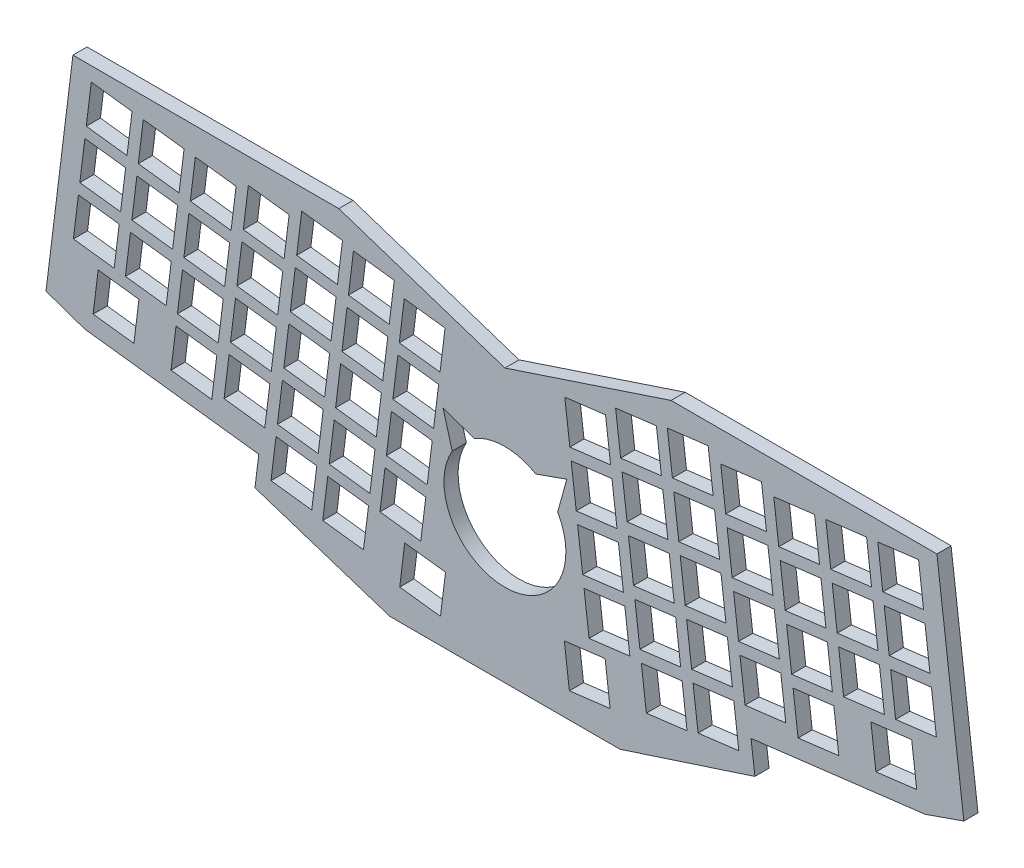
SolidWorks part; units mm, degrees
ref_plane "Спереди" through (0, 0, 0) normal (0, 0, 1) x (1, 0, 0)
ref_plane "Сверху" through (0, 0, 0) normal (0, 1, 0) x (1, 0, 0)
ref_plane "Справа" through (0, 0, 0) normal (1, 0, 0) x (0, 0, -1)
sketch "Контур" plane through (0, 0, 0) normal (0, 0, 1) x (1, 0, 0)
  line L0 (148.3547, -23.6716) -> (86.886, -31.2162)
  line L1 (162, -18.92) -> (148.3547, -23.6716)
  line L2 (-152.5, 58) -> (-58.64, 58)
  line L3 (86.886, -31.2162) -> (88.2371, -42.1562)
  line L4 (-10.9082, 11.6263) -> (-21.8482, 15.5133)
  line L5 (152.5, 58) -> (162, -18.92)
  line L6 (-88.2371, -42.1562) -> (-40.5971, -57.6623)
  line L7 (-58.64, 58) -> (0, 38.59)
  line L8 (-152.5, 58) -> (-162, -18.92)
  line L9 (58.64, 58) -> (0, 38.59)
  line L10 (-86.886, -31.2162) -> (-88.2371, -42.1562)
  line L11 (-40.5971, -57.6623) -> (40.5971, -57.6623)
  line L12 (-162, -18.92) -> (-148.3547, -23.6716)
  line L13 (0, 0) -> (0, -106.1018) construction
  line L14 (-148.3547, -23.6716) -> (-86.886, -31.2162)
  line L15 (88.2371, -42.1562) -> (40.5971, -57.6623)
  line L16 (152.5, 58) -> (58.64, 58)
  line L17 (-21.8482, 15.5133) -> (-18.6176, 3.8733)
  line L18 (21.8482, 15.5133) -> (18.6176, 3.8733)
  line L19 (10.9082, 11.6263) -> (21.8482, 15.5133)
  arc A0 (-18.6176, 3.8733) -> (18.6176, 3.8733) centre (0, -6.93) ccw
  arc A2 (10.9082, 11.6263) -> (-10.9082, 11.6263) centre (0, -6.93) ccw
  point P0 (0, 0)
  point P19 (0, -57.6623)
  dimension "D1" = 43.05
  dimension "D2" = 10.94
  dimension "D3" = 61.4687
  dimension "D6" = 47.64
  dimension "D7" = 50.1
  dimension "D8" = 11.64
  dimension "D9" = 12.08
  dimension "D10" = 11.61
  dimension "D11" = 45.52
sketch "Эскиз4" plane through (0, 0, 0) normal (0, 0, 1) x (1, 0, 0)
  line L0 (21.8482, 15.5133) -> (18.6176, 3.8733) construction
  line L1 (10.9082, 11.6263) -> (21.8482, 15.5133) construction
  line L2 (-10.9082, 11.6263) -> (-21.8482, 15.5133) construction
  line L3 (-21.8482, 15.5133) -> (-18.6176, 3.8733) construction
  line L4 (21.8482, 15.5133) -> (18.6176, 3.8733)
  line L5 (10.9082, 11.6263) -> (21.8482, 15.5133)
  line L6 (-10.9082, 11.6263) -> (-21.8482, 15.5133)
  line L7 (-21.8482, 15.5133) -> (-18.6176, 3.8733)
  line L12 (-21.8482, 15.5133) -> (-18.6176, 3.8733)
  line L13 (-21.8482, 15.5133) -> (-18.6176, 3.8733)
  line L14 (-10.9082, 11.6263) -> (-21.8482, 15.5133)
  line L15 (152.5, 58) -> (58.64, 58)
  line L16 (58.64, 58) -> (0, 38.59)
  line L17 (0, 38.59) -> (-58.64, 58)
  line L18 (-58.64, 58) -> (-152.5, 58)
  line L19 (-152.5, 58) -> (-162, -18.92)
  line L20 (-162, -18.92) -> (-148.3547, -23.6716)
  line L21 (-148.3547, -23.6716) -> (-86.886, -31.2162)
  line L22 (-86.886, -31.2162) -> (-88.2371, -42.1562)
  line L23 (-88.2371, -42.1562) -> (-40.5971, -57.6623)
  line L24 (-40.5971, -57.6623) -> (40.5971, -57.6623)
  line L25 (40.5971, -57.6623) -> (88.2371, -42.1562)
  line L26 (88.2371, -42.1562) -> (86.886, -31.2162)
  line L27 (86.886, -31.2162) -> (148.3547, -23.6716)
  line L28 (148.3547, -23.6716) -> (162, -18.92)
  line L29 (162, -18.92) -> (152.5, 58)
  line L30 (152.5, 58) -> (58.64, 58)
  line L31 (58.64, 58) -> (0, 38.59)
  line L32 (0, 38.59) -> (-58.64, 58)
  line L33 (-58.64, 58) -> (-152.5, 58)
  line L34 (-152.5, 58) -> (-162, -18.92)
  line L35 (-162, -18.92) -> (-148.3547, -23.6716)
  line L36 (-148.3547, -23.6716) -> (-86.886, -31.2162)
  line L37 (-86.886, -31.2162) -> (-88.2371, -42.1562)
  line L38 (-88.2371, -42.1562) -> (-40.5971, -57.6623)
  line L39 (-40.5971, -57.6623) -> (40.5971, -57.6623)
  line L40 (40.5971, -57.6623) -> (88.2371, -42.1562)
  line L41 (88.2371, -42.1562) -> (86.886, -31.2162)
  line L42 (86.886, -31.2162) -> (148.3547, -23.6716)
  line L43 (148.3547, -23.6716) -> (162, -18.92)
  line L44 (162, -18.92) -> (152.5, 58)
  line L45 (-10.9082, 11.6263) -> (-21.8482, 15.5133)
  line L46 (21.8482, 15.5133) -> (10.9082, 11.6263)
  line L47 (21.8482, 15.5133) -> (10.9082, 11.6263)
  line L48 (18.6176, 3.8733) -> (21.8482, 15.5133)
  line L49 (18.6176, 3.8733) -> (21.8482, 15.5133)
  arc A1 (-18.6176, 3.8733) -> (18.6176, 3.8733) centre (0, -6.93) ccw
  arc A2 (-18.6176, 3.8733) -> (18.6176, 3.8733) centre (0, -6.93) ccw
  arc A3 (10.9082, 11.6263) -> (-10.9082, 11.6263) centre (0, -6.93) ccw
  arc A6 (10.9082, 11.6263) -> (-10.9082, 11.6263) centre (0, -6.93) ccw
  arc A7 (10.9082, 11.6263) -> (-10.9082, 11.6263) centre (0, -6.93) ccw
  dimension "D1" = 0
  dimension "D2" = 0
extrude "Бобышка-Вытянуть2" add sketch "Эскиз4" along normal blind 5 contours L43 L44 L30 L31 L32 L33 L34 L35 L36 L37 L38 L39 L40 L41 L42 A2 L5 L4 L7 L6
sketch "Эскиз5" plane through (0, 0, 5) normal (0, 0, 1) x (1, 0, 0)
sketch "Эскиз6" plane through (0, 0, 5) normal (0, 0, 1) x (1, 0, 0)
  line L1 (147.2152, -18.7739) -> (81.3104, -26.863) construction
  line L2 (154.5624, -16.2154) -> (147.2152, -18.7739) construction
  line L3 (-146.014, 53) -> (-59.446, 53) construction
  line L4 (81.3104, -26.863) -> (82.7695, -38.6776) construction
  line L5 (146.014, 53) -> (154.5624, -16.2154) construction
  line L6 (-82.7695, -38.6776) -> (-39.8039, -52.6623) construction
  line L7 (-59.446, 53) -> (0, 33.3232) construction
  line L8 (-146.014, 53) -> (-154.5624, -16.2154) construction
  line L9 (59.446, 53) -> (0, 33.3232) construction
  line L10 (-81.3104, -26.863) -> (-82.7695, -38.6776) construction
  line L11 (-39.8039, -52.6623) -> (39.8039, -52.6623) construction
  line L12 (-154.5624, -16.2154) -> (-147.2152, -18.7739) construction
  line L13 (-147.2152, -18.7739) -> (-81.3104, -26.863) construction
  line L14 (82.7695, -38.6776) -> (39.8039, -52.6623) construction
  line L15 (146.014, 53) -> (59.446, 53) construction
  line L16 (-88.2371, -42.1562) -> (-40.5971, -57.6623) construction
  line L17 (-86.886, -31.2162) -> (-88.2371, -42.1562) construction
  line L18 (-148.3547, -23.6716) -> (-86.886, -31.2162) construction
  line L19 (-162, -18.92) -> (-148.3547, -23.6716) construction
  line L20 (-152.5, 58) -> (-162, -18.92) construction
  line L21 (-152.5, 58) -> (-58.64, 58) construction
  line L22 (152.5, 58) -> (162, -18.92) construction
  line L23 (88.2371, -42.1562) -> (40.5971, -57.6623) construction
  line L24 (86.886, -31.2162) -> (88.2371, -42.1562) construction
  line L25 (148.3547, -23.6716) -> (86.886, -31.2162) construction
  line L26 (-148.2816, 34.6395) -> (-150.0589, 20.2488)
  line L27 (162, -18.92) -> (148.3547, -23.6716) construction
  line L28 (-58.64, 58) -> (0, 38.59) construction
  line L29 (-148.2816, 34.6395) -> (-133.8909, 32.8622)
  line L30 (58.64, 58) -> (0, 38.59) construction
  line L31 (-150.0589, 20.2488) -> (-135.6682, 18.4715)
  line L32 (-133.8909, 32.8622) -> (-135.6682, 18.4715)
  line L33 (-152.3265, 1.8883) -> (-137.9358, 0.111)
  line L34 (-150.5492, 16.279) -> (-152.3265, 1.8883)
  line L35 (-146.014, 53) -> (-147.7913, 38.6093)
  line L36 (-146.014, 53) -> (-131.6233, 51.2227)
  line L37 (-147.7913, 38.6093) -> (-133.4006, 36.832)
  line L38 (-131.6233, 51.2227) -> (-133.4006, 36.832)
  line L39 (-136.1585, 14.5017) -> (-137.9358, 0.111)
  line L40 (-150.5492, 16.279) -> (-136.1585, 14.5017)
  line L41 (-145.3642, -17.6121) -> (-130.9736, -19.3894)
  line L42 (-129.1963, -4.9988) -> (-130.9736, -19.3894)
  line L43 (-143.5869, -3.2214) -> (-129.1963, -4.9988)
  line L44 (-143.5869, -3.2214) -> (-145.3642, -17.6121)
  line L45 (-132.1887, 14.0114) -> (-117.798, 12.2341)
  line L46 (-113.2628, 48.9551) -> (-115.0401, 34.5644)
  line L47 (-129.4308, 36.3417) -> (-115.0401, 34.5644)
  line L48 (-127.6535, 50.7324) -> (-113.2628, 48.9551)
  line L49 (-117.798, 12.2341) -> (-119.5753, -2.1566)
  line L50 (-127.6535, 50.7324) -> (-129.4308, 36.3417)
  line L51 (-129.9211, 32.3719) -> (-115.5304, 30.5946)
  line L52 (-129.9211, 32.3719) -> (-131.6984, 17.9812)
  line L53 (-133.966, -0.3793) -> (-119.5753, -2.1566)
  line L54 (-115.5304, 30.5946) -> (-117.3077, 16.2039)
  line L55 (-132.1887, 14.0114) -> (-133.966, -0.3793)
  line L56 (-131.6984, 17.9812) -> (-117.3077, 16.2039)
  line L57 (-109.293, 48.4648) -> (-111.0703, 34.0741)
  line L58 (-109.293, 48.4648) -> (-94.9023, 46.6875)
  line L59 (-97.1699, 28.327) -> (-98.9472, 13.9363)
  line L60 (-94.9023, 46.6875) -> (-96.6796, 32.2968)
  line L61 (-113.3379, 15.7136) -> (-98.9472, 13.9363)
  line L62 (-115.6055, -2.6469) -> (-101.2148, -4.4242)
  line L63 (-99.4375, 9.9665) -> (-101.2148, -4.4242)
  line L64 (-111.5606, 30.1043) -> (-97.1699, 28.327)
  line L65 (-113.8282, 11.7438) -> (-99.4375, 9.9665)
  line L66 (-113.8282, 11.7438) -> (-115.6055, -2.6469)
  line L67 (-111.0703, 34.0741) -> (-96.6796, 32.2968)
  line L68 (-111.5606, 30.1043) -> (-113.3379, 15.7136)
  line L69 (-117.8731, -21.0074) -> (-103.4825, -22.7847)
  line L70 (-101.7051, -8.394) -> (-103.4825, -22.7847)
  line L71 (-116.0958, -6.6167) -> (-117.8731, -21.0074)
  line L72 (-116.0958, -6.6167) -> (-101.7051, -8.394)
  line L73 (-78.4461, 29.0011) -> (-80.2234, 14.6105)
  line L74 (-92.3465, 34.7483) -> (-77.9558, 32.971)
  line L75 (-97.372, -5.9425) -> (-99.1493, -20.3332)
  line L76 (-92.8367, 30.7785) -> (-78.4461, 29.0011)
  line L77 (-76.1785, 47.3616) -> (-77.9558, 32.971)
  line L78 (-96.8817, -1.9727) -> (-82.491, -3.75)
  line L79 (-94.6141, 16.3878) -> (-80.2234, 14.6105)
  line L80 (-97.372, -5.9425) -> (-82.9813, -7.7198)
  line L81 (-82.9813, -7.7198) -> (-84.7586, -22.1105)
  line L82 (-80.7137, 10.6406) -> (-82.491, -3.75)
  line L83 (-99.1493, -20.3332) -> (-84.7586, -22.1105)
  line L84 (-90.5691, 49.139) -> (-76.1785, 47.3616)
  line L85 (-95.1044, 12.418) -> (-80.7137, 10.6406)
  line L86 (-95.1044, 12.418) -> (-96.8817, -1.9727)
  line L87 (-90.5691, 49.139) -> (-92.3465, 34.7483)
  line L88 (-92.8367, 30.7785) -> (-94.6141, 16.3878)
  line L89 (-76.2674, 13.9695) -> (-61.8767, 12.1922)
  line L90 (-78.535, -4.391) -> (-64.1443, -6.1683)
  line L91 (-73.9997, 32.33) -> (-59.6091, 30.5527)
  line L92 (-76.2674, 13.9695) -> (-78.0447, -0.4212)
  line L93 (-73.9997, 32.33) -> (-75.7771, 17.9393)
  line L94 (-59.6091, 30.5527) -> (-61.3864, 16.162)
  line L95 (-64.1443, -6.1683) -> (-65.9216, -20.559)
  line L96 (-57.3415, 48.9132) -> (-59.1188, 34.5225)
  line L97 (-78.0447, -0.4212) -> (-63.654, -2.1985)
  line L98 (-78.535, -4.391) -> (-80.3123, -18.7817)
  line L99 (-71.7321, 50.6905) -> (-57.3415, 48.9132)
  line L100 (-71.7321, 50.6905) -> (-73.5094, 36.2998)
  line L101 (-80.3123, -18.7817) -> (-65.9216, -20.559)
  line L102 (-75.7771, 17.9393) -> (-61.3864, 16.162)
  line L103 (-73.5094, 36.2998) -> (-59.1188, 34.5225)
  line L104 (-61.8767, 12.1922) -> (-63.654, -2.1985)
  line L105 (-80.8026, -22.7515) -> (-66.4119, -24.5288)
  line L106 (-80.8026, -22.7515) -> (-82.5799, -37.1422)
  line L107 (-82.5799, -37.1422) -> (-68.1892, -38.9195)
  line L108 (-66.4119, -24.5288) -> (-68.1892, -38.9195)
  line L109 (-62.5374, -25.7908) -> (-64.3147, -40.1814)
  line L110 (-59.7795, -3.4604) -> (-45.3888, -5.2377)
  line L111 (-48.1467, -27.5681) -> (-49.924, -41.9587)
  line L112 (-43.6115, 9.1529) -> (-45.3888, -5.2377)
  line L113 (-60.2698, -7.4303) -> (-62.0471, -21.8209)
  line L114 (-60.2698, -7.4303) -> (-45.8791, -9.2076)
  line L115 (-55.2442, 33.2606) -> (-40.8536, 31.4833)
  line L116 (-53.4669, 47.6512) -> (-55.2442, 33.2606)
  line L117 (-45.8791, -9.2076) -> (-47.6564, -23.5982)
  line L118 (-62.5374, -25.7908) -> (-48.1467, -27.5681)
  line L119 (-55.7345, 29.2907) -> (-57.5119, 14.9001)
  line L120 (-58.0022, 10.9302) -> (-43.6115, 9.1529)
  line L121 (-62.0471, -21.8209) -> (-47.6564, -23.5982)
  line L122 (-41.3439, 27.5134) -> (-43.1212, 13.1228)
  line L123 (-57.5119, 14.9001) -> (-43.1212, 13.1228)
  line L124 (-39.0763, 45.8739) -> (-40.8536, 31.4833)
  line L125 (-58.0022, 10.9302) -> (-59.7795, -3.4604)
  line L126 (-55.7345, 29.2907) -> (-41.3439, 27.5134)
  line L127 (-64.3147, -40.1814) -> (-49.924, -41.9587)
  line L128 (-53.4669, 47.6512) -> (-39.0763, 45.8739)
  line L129 (-25.6652, 3.5315) -> (-27.4425, -10.8592)
  line L130 (-27.9328, -14.829) -> (-29.7101, -29.2197)
  line L131 (-35.3612, -32.5522) -> (-37.1385, -46.9428)
  line L132 (-23.3976, 21.892) -> (-25.1749, 7.5013)
  line L133 (-40.0559, 5.3088) -> (-25.6652, 3.5315)
  line L134 (-37.298, 27.6391) -> (-22.9073, 25.8618)
  line L135 (-21.13, 40.2525) -> (-22.9073, 25.8618)
  line L136 (-41.8332, -9.0819) -> (-27.4425, -10.8592)
  line L137 (-35.3612, -32.5522) -> (-20.9706, -34.3295)
  line L138 (-39.5656, 9.2786) -> (-25.1749, 7.5013)
  line L139 (-42.3235, -13.0517) -> (-27.9328, -14.829)
  line L140 (-44.1008, -27.4424) -> (-29.7101, -29.2197)
  line L141 (-37.7883, 23.6693) -> (-23.3976, 21.892)
  line L142 (-40.0559, 5.3088) -> (-41.8332, -9.0819)
  line L143 (-42.3235, -13.0517) -> (-44.1008, -27.4424)
  line L144 (-35.5206, 42.0298) -> (-37.298, 27.6391)
  line L145 (-37.7883, 23.6693) -> (-39.5656, 9.2786)
  line L146 (-20.9706, -34.3295) -> (-22.7479, -48.7201)
  line L147 (-37.1385, -46.9428) -> (-22.7479, -48.7201)
  line L148 (-35.5206, 42.0298) -> (-21.13, 40.2525)
  line L151 (35.5206, 42.0298) -> (21.13, 40.2525)
  line L152 (37.1385, -46.9428) -> (22.7479, -48.7201)
  line L153 (20.9706, -34.3295) -> (22.7479, -48.7201)
  line L154 (37.7883, 23.6693) -> (39.5656, 9.2786)
  line L155 (35.5206, 42.0298) -> (37.298, 27.6391)
  line L156 (42.3235, -13.0517) -> (44.1008, -27.4424)
  line L157 (40.0559, 5.3088) -> (41.8332, -9.0819)
  line L158 (37.7883, 23.6693) -> (23.3976, 21.892)
  line L159 (44.1008, -27.4424) -> (29.7101, -29.2197)
  line L160 (42.3235, -13.0517) -> (27.9328, -14.829)
  line L161 (39.5656, 9.2786) -> (25.1749, 7.5013)
  line L162 (35.3612, -32.5522) -> (20.9706, -34.3295)
  line L163 (41.8332, -9.0819) -> (27.4425, -10.8592)
  line L164 (21.13, 40.2525) -> (22.9073, 25.8618)
  line L165 (37.298, 27.6391) -> (22.9073, 25.8618)
  line L166 (40.0559, 5.3088) -> (25.6652, 3.5315)
  line L167 (23.3976, 21.892) -> (25.1749, 7.5013)
  line L168 (35.3612, -32.5522) -> (37.1385, -46.9428)
  line L169 (27.9328, -14.829) -> (29.7101, -29.2197)
  line L170 (25.6652, 3.5315) -> (27.4425, -10.8592)
  line L171 (53.4669, 47.6512) -> (39.0763, 45.8739)
  line L172 (64.3147, -40.1814) -> (49.924, -41.9587)
  line L173 (55.7345, 29.2907) -> (41.3439, 27.5134)
  line L174 (58.0022, 10.9302) -> (59.7795, -3.4604)
  line L175 (39.0763, 45.8739) -> (40.8536, 31.4833)
  line L176 (57.5119, 14.9001) -> (43.1212, 13.1228)
  line L177 (41.3439, 27.5134) -> (43.1212, 13.1228)
  line L178 (62.0471, -21.8209) -> (47.6564, -23.5982)
  line L179 (58.0022, 10.9302) -> (43.6115, 9.1529)
  line L180 (55.7345, 29.2907) -> (57.5119, 14.9001)
  line L181 (62.5374, -25.7908) -> (48.1467, -27.5681)
  line L182 (45.8791, -9.2076) -> (47.6564, -23.5982)
  line L183 (53.4669, 47.6512) -> (55.2442, 33.2606)
  line L184 (55.2442, 33.2606) -> (40.8536, 31.4833)
  line L185 (60.2698, -7.4303) -> (45.8791, -9.2076)
  line L186 (60.2698, -7.4303) -> (62.0471, -21.8209)
  line L187 (43.6115, 9.1529) -> (45.3888, -5.2377)
  line L188 (48.1467, -27.5681) -> (49.924, -41.9587)
  line L189 (59.7795, -3.4604) -> (45.3888, -5.2377)
  line L190 (62.5374, -25.7908) -> (64.3147, -40.1814)
  line L191 (66.4119, -24.5288) -> (68.1892, -38.9195)
  line L192 (82.5799, -37.1422) -> (68.1892, -38.9195)
  line L193 (80.8026, -22.7515) -> (82.5799, -37.1422)
  line L194 (80.8026, -22.7515) -> (66.4119, -24.5288)
  line L195 (61.8767, 12.1922) -> (63.654, -2.1985)
  line L196 (73.5094, 36.2998) -> (59.1188, 34.5225)
  line L197 (75.7771, 17.9393) -> (61.3864, 16.162)
  line L198 (80.3123, -18.7817) -> (65.9216, -20.559)
  line L199 (71.7321, 50.6905) -> (73.5094, 36.2998)
  line L200 (71.7321, 50.6905) -> (57.3415, 48.9132)
  line L201 (78.535, -4.391) -> (80.3123, -18.7817)
  line L202 (78.0447, -0.4212) -> (63.654, -2.1985)
  line L203 (57.3415, 48.9132) -> (59.1188, 34.5225)
  line L204 (64.1443, -6.1683) -> (65.9216, -20.559)
  line L205 (59.6091, 30.5527) -> (61.3864, 16.162)
  line L206 (73.9997, 32.33) -> (75.7771, 17.9393)
  line L207 (76.2674, 13.9695) -> (78.0447, -0.4212)
  line L208 (73.9997, 32.33) -> (59.6091, 30.5527)
  line L209 (78.535, -4.391) -> (64.1443, -6.1683)
  line L210 (76.2674, 13.9695) -> (61.8767, 12.1922)
  line L211 (92.8367, 30.7785) -> (94.6141, 16.3878)
  line L212 (90.5691, 49.139) -> (92.3465, 34.7483)
  line L213 (95.1044, 12.418) -> (96.8817, -1.9727)
  line L214 (95.1044, 12.418) -> (80.7137, 10.6406)
  line L215 (90.5691, 49.139) -> (76.1785, 47.3616)
  line L216 (99.1493, -20.3332) -> (84.7586, -22.1105)
  line L217 (80.7137, 10.6406) -> (82.491, -3.75)
  line L218 (82.9813, -7.7198) -> (84.7586, -22.1105)
  line L219 (97.372, -5.9425) -> (82.9813, -7.7198)
  line L220 (94.6141, 16.3878) -> (80.2234, 14.6105)
  line L221 (96.8817, -1.9727) -> (82.491, -3.75)
  line L222 (76.1785, 47.3616) -> (77.9558, 32.971)
  line L223 (92.8367, 30.7785) -> (78.4461, 29.0011)
  line L224 (97.372, -5.9425) -> (99.1493, -20.3332)
  line L225 (92.3465, 34.7483) -> (77.9558, 32.971)
  line L226 (78.4461, 29.0011) -> (80.2234, 14.6105)
  line L227 (116.0958, -6.6167) -> (101.7051, -8.394)
  line L228 (116.0958, -6.6167) -> (117.8731, -21.0074)
  line L229 (101.7051, -8.394) -> (103.4825, -22.7847)
  line L230 (117.8731, -21.0074) -> (103.4825, -22.7847)
  line L231 (111.5606, 30.1043) -> (113.3379, 15.7136)
  line L232 (111.0703, 34.0741) -> (96.6796, 32.2968)
  line L233 (113.8282, 11.7438) -> (115.6055, -2.6469)
  line L234 (113.8282, 11.7438) -> (99.4375, 9.9665)
  line L235 (111.5606, 30.1043) -> (97.1699, 28.327)
  line L236 (99.4375, 9.9665) -> (101.2148, -4.4242)
  line L237 (115.6055, -2.6469) -> (101.2148, -4.4242)
  line L238 (113.3379, 15.7136) -> (98.9472, 13.9363)
  line L239 (94.9023, 46.6875) -> (96.6796, 32.2968)
  line L240 (97.1699, 28.327) -> (98.9472, 13.9363)
  line L241 (109.293, 48.4648) -> (94.9023, 46.6875)
  line L242 (109.293, 48.4648) -> (111.0703, 34.0741)
  line L243 (131.6984, 17.9812) -> (117.3077, 16.2039)
  line L244 (132.1887, 14.0114) -> (133.966, -0.3793)
  line L245 (115.5304, 30.5946) -> (117.3077, 16.2039)
  line L246 (133.966, -0.3793) -> (119.5753, -2.1566)
  line L247 (129.9211, 32.3719) -> (131.6984, 17.9812)
  line L248 (129.9211, 32.3719) -> (115.5304, 30.5946)
  line L249 (127.6535, 50.7324) -> (129.4308, 36.3417)
  line L250 (117.798, 12.2341) -> (119.5753, -2.1566)
  line L251 (127.6535, 50.7324) -> (113.2628, 48.9551)
  line L252 (129.4308, 36.3417) -> (115.0401, 34.5644)
  line L253 (113.2628, 48.9551) -> (115.0401, 34.5644)
  line L254 (132.1887, 14.0114) -> (117.798, 12.2341)
  line L255 (143.5869, -3.2214) -> (145.3642, -17.6121)
  line L256 (143.5869, -3.2214) -> (129.1963, -4.9988)
  line L257 (129.1963, -4.9988) -> (130.9736, -19.3894)
  line L258 (145.3642, -17.6121) -> (130.9736, -19.3894)
  line L259 (150.5492, 16.279) -> (136.1585, 14.5017)
  line L260 (136.1585, 14.5017) -> (137.9358, 0.111)
  line L261 (131.6233, 51.2227) -> (133.4006, 36.832)
  line L262 (147.7913, 38.6093) -> (133.4006, 36.832)
  line L263 (146.014, 53) -> (131.6233, 51.2227)
  line L264 (146.014, 53) -> (147.7913, 38.6093)
  line L265 (150.5492, 16.279) -> (152.3265, 1.8883)
  line L266 (152.3265, 1.8883) -> (137.9358, 0.111)
  line L267 (133.8909, 32.8622) -> (135.6682, 18.4715)
  line L268 (150.0589, 20.2488) -> (135.6682, 18.4715)
  line L269 (148.2816, 34.6395) -> (133.8909, 32.8622)
  line L270 (148.2816, 34.6395) -> (150.0589, 20.2488)
  line L271 (152.5, 58) -> (58.64, 58) construction
  point P13 (0, -52.6623)
  dimension "D1" = 0
  dimension "D2" = 5
  dimension "D4" = 5
  dimension "D5" = 5
  dimension "D6" = 5
  dimension "D7" = 5
  dimension "D8" = 5
  dimension "D9" = 7.05
  dimension "D10" = 5
  dimension "D11" = 5
  dimension "D12" = 5
  dimension "D13" = 5
  dimension "D14" = 5
  dimension "D15" = 5
  dimension "D16" = 14.5
  dimension "D17" = 14.5
  dimension "D18" = 14.5
  dimension "D19" = 14.5
  dimension "D20" = 4
  dimension "D21" = 4
  dimension "D22" = 4
  dimension "D23" = 5.2
  dimension "D24" = 0
  dimension "D25" = 4
  dimension "D26" = 0
  dimension "D27" = 4
  dimension "D28" = 0
  dimension "D29" = 4
  dimension "D30" = 0
  dimension "D31" = 0
  dimension "D32" = 0
  dimension "D33" = 4
  dimension "D34" = 4
  dimension "D35" = 4
  dimension "D36" = 4
  dimension "D37" = 0
  dimension "D38" = 0
  dimension "D39" = 4
  dimension "D40" = 0
  dimension "D41" = 0
  dimension "D42" = 4
  dimension "D43" = 4
  dimension "D44" = 4
  dimension "D45" = 0
  dimension "D46" = 0
  dimension "D47" = 0
  dimension "D48" = 0
  dimension "D49" = 4.0048
  dimension "D50" = 4
  dimension "D51" = 0
  dimension "D52" = 0
  dimension "D53" = 0
  dimension "D54" = 0
  dimension "D55" = 4
  dimension "D56" = 0
  dimension "D57" = 4
  dimension "D58" = 4
  dimension "D59" = 4
  dimension "D60" = 4
  dimension "D61" = 0
  dimension "D62" = 0
  dimension "D63" = 4
  dimension "D64" = 5.2
  dimension "D65" = 4
  dimension "D66" = 4
  dimension "D67" = 4
  dimension "D68" = 4
  dimension "D69" = 14.5
  dimension "D70" = 14.5
  dimension "D71" = 7.05
  dimension "D72" = 5.2
other "Выровнять группу1"
other "Выровнять группу2"
extrude "Вырез-Вытянуть5" cut sketch "Эскиз6" against normal through all
